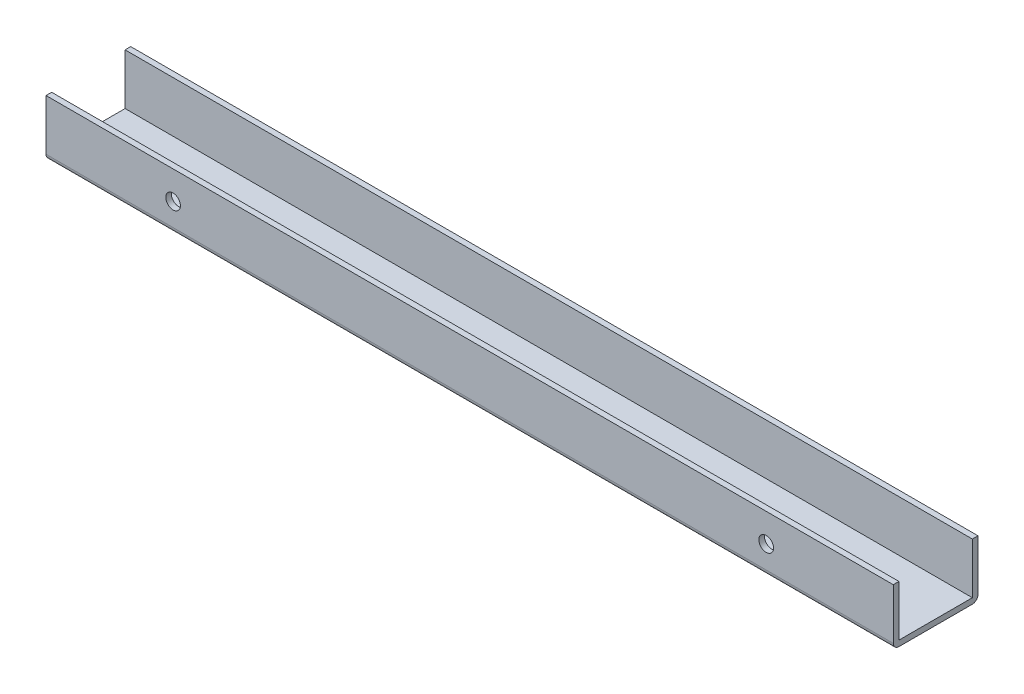
SolidWorks part; units mm, degrees
ref_plane "Front Plane" through (0, 0, 0) normal (0, 0, 1) x (1, 0, 0)
ref_plane "Top Plane" through (0, 0, 0) normal (0, 1, 0) x (1, 0, 0)
ref_plane "Right Plane" through (0, 0, 0) normal (1, 0, 0) x (0, 0, -1)
sketch "Sketch1" plane through (0, 0, 0) normal (1, 0, 0) x (0, 0, -1)
  line L0 (140, 10) -> (140, 100)
  line L1 (10, 0) -> (140, 0)
  line L2 (0, 10) -> (0, 100)
  line L3 (10, 10) -> (140, 10)
  line L4 (150, 10) -> (150, 100)
  line L5 (10, 10) -> (10, 100)
  line L6 (0, 100) -> (10, 100)
  line L7 (140, 100) -> (150, 100)
  arc A0 (10, 0) -> (0, 10) centre (10, 10) cw
  arc A1 (140, 0) -> (150, 10) centre (140, 10) ccw
  point P6 (0, 0)
  point P9 (150, 0)
  dimension "D3" = 10
  dimension "D1" = 100
  dimension "Width" = 150
extrude "Extrude1" add sketch "Sketch1" along normal blind 1500
sketch "Sketch2" plane through (0, 0, 0) normal (0, 0, 1) x (1, 0, 0)
  line L4 (1500, 100) -> (1500, 10) construction
  line L5 (0, 100) -> (0, 10) construction
  line L6 (1500, 0) -> (0, 0) construction
  circle A0 centre (225, 50) radius 13
  circle A1 centre (1275, 50) radius 13
  dimension "D1" = 225
  dimension "D2" = 26
  dimension "D3" = 26
  dimension "D4" = 225
  dimension "D5" = 50
  dimension "D6" = 50
extrude "Cut-Extrude1" cut sketch "Sketch2" against normal blind 10
